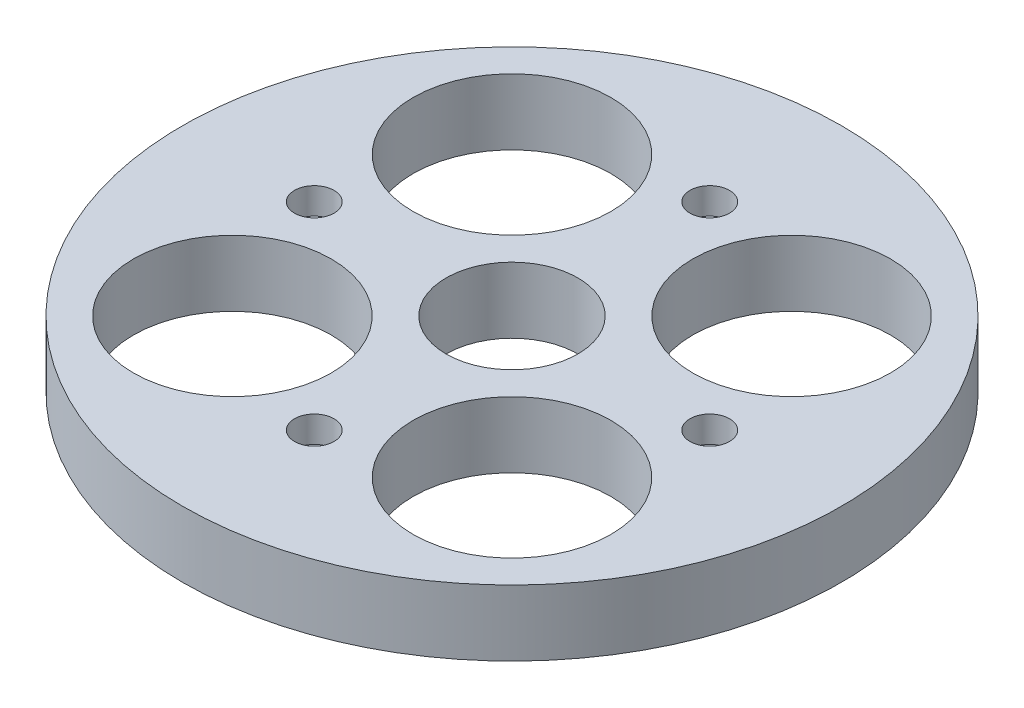
SolidWorks part; units mm, degrees
ref_plane "前视基准面" through (0, 0, 0) normal (0, 0, 1) x (1, 0, 0)
ref_plane "上视基准面" through (0, 0, 0) normal (0, 1, 0) x (1, 0, 0)
ref_plane "右视基准面" through (0, 0, 0) normal (1, 0, 0) x (0, 0, -1)
other "Configuration Table"
sketch "草图2" plane through (0, 0, 0) normal (0, 1, 0) x (1, 0, 0)
  circle A0 centre (0, 0) radius 50
  circle A1 centre (0, 0) radius 10
  circle A2 centre (0, 0) radius 30
  dimension "D1" = 100
  dimension "D2" = 20
  dimension "D3" = 60
extrude "凸台-拉伸1" add sketch "草图2" along normal blind 10 contours A0 A2 | A2 A1
sketch "草图3" plane through (0, 10, 0) normal (0, 1, 0) x (1, 0, 0)
  line L0 (0, -1000) -> (0, 49000) construction
  circle A0 centre (0, 0) radius 30
  circle A1 centre (0, 30) radius 3
  circle A2 centre (30, 0) radius 3
  circle A3 centre (0, -30) radius 3
  circle A4 centre (-30, 0) radius 3
  dimension "D1" = 6
  dimension "D2" = 4
extrude "切除-拉伸1" cut sketch "草图3" against normal blind 4 contours A1 L0 A0 | L0 A1 A0 | L0 A0 A1 | A0 L0 A1 | A0 A2 | A0 A2 | A0 A4 | A0 A4 | A0 L0 A3 | L0 A0 A3 | L0 A3 A0 | A3 L0 A0
sketch "草图4" plane through (0, 6, 0) normal (0, 1, 0) x (1, 0, 0)
  circle A0 centre (0, 30) radius 1.5
  circle A1 centre (30, 0) radius 1.5
  circle A2 centre (0, -30) radius 1.5
  circle A3 centre (-30, 0) radius 1.5
  dimension "D1" = 3
  dimension "D2" = 4
extrude "切除-拉伸2" cut sketch "草图4" against normal through all
sketch "草图5" plane through (0, 0, 0) normal (0, -1, 0) x (1, 0, 0)
  circle A0 centre (0, 30) radius 3
  circle A1 centre (30, 0) radius 3
  circle A2 centre (0, -30) radius 3
  circle A3 centre (-30, 0) radius 3
  dimension "D1" = 6
  dimension "D2" = 4
extrude "切除-拉伸3" cut sketch "草图5" against normal blind 3
sketch "草图6" plane through (0, 10, 0) normal (0, 1, 0) x (1, 0, 0)
  line L0 (-707.1068, -707.1068) -> (34648.2323, 34648.2323)
  circle A0 centre (0, 0) radius 10
  circle A1 centre (0, 0) radius 50
  circle A2 centre (0, 0) radius 45
  circle A3 centre (0, 0) radius 15
  circle A4 centre (21.2132, 21.2132) radius 15
  circle A5 centre (0, 0) radius 30 construction
  circle A6 centre (21.2132, -21.2132) radius 15
  circle A7 centre (-21.2132, -21.2132) radius 15
  circle A8 centre (-21.2132, 21.2132) radius 15
  point P23 (0, 0)
  dimension "D1" = 5
  dimension "D2" = 5
  dimension "D3" = 4
extrude "切除-拉伸5" cut sketch "草图6" against normal through all contours A8 | L0 A4 | L0 A4 | A6 | L0 A7 | L0 A7
